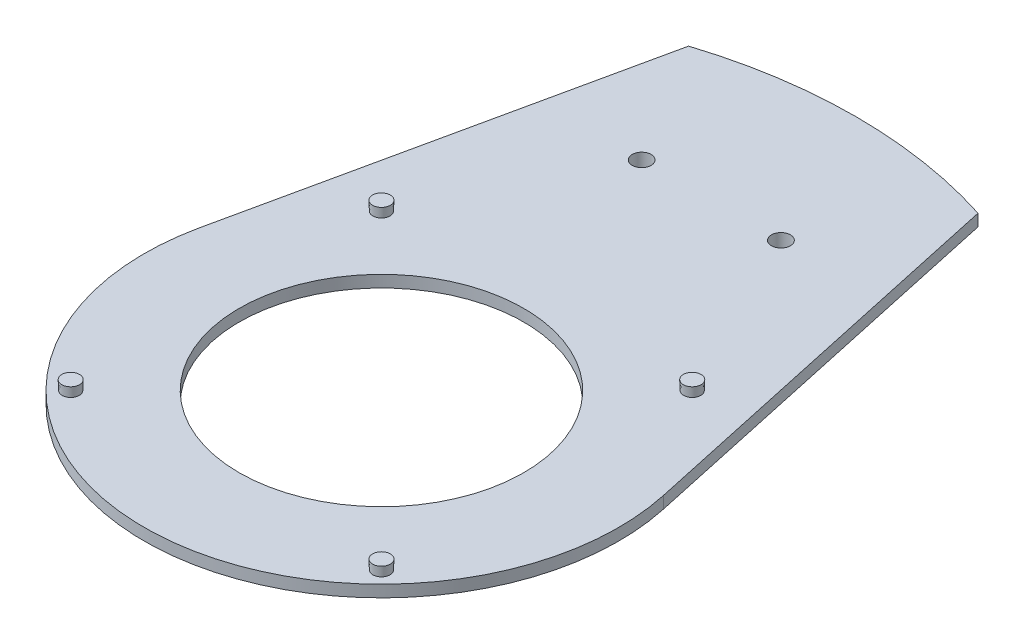
SolidWorks part; units mm, degrees
ref_plane "Front Plane" through (0, 0, 0) normal (0, 0, 1) x (1, 0, 0)
ref_plane "Top Plane" through (0, 0, 0) normal (0, 1, 0) x (1, 0, 0)
ref_plane "Right Plane" through (0, 0, 0) normal (1, 0, 0) x (0, 0, -1)
sketch "Sketch1" plane through (0, 0, 0) normal (0, 1, 0) x (1, 0, 0)
  line L7 (-38, -38) -> (38, -38) construction
  line L8 (-38, -38) -> (-38, 38) construction
  line L9 (-38, 38) -> (38, 38) construction
  line L10 (38, -38) -> (38, 38) construction
  circle A0 centre (0, 0) radius 30
  circle A1 centre (0, 0) radius 100
  point P32 (0, 0)
  dimension "D1" = 60
  dimension "D3" = 200
  dimension "D2" = 76
extrude "Boss-Extrude1" add sketch "Sketch1" along normal blind 2.5
sketch "Sketch2" plane through (0, 2.5, 0) normal (0, 1, 0) x (1, 0, 0)
  line L0 (-32.75, -38) -> (-32.75, 38) construction
  line L3 (-38, 32.75) -> (38, 32.75) construction
  line L6 (32.75, -38) -> (32.75, 38) construction
  line L7 (-38, -32.75) -> (38, -32.75) construction
  line L9 (-38, -38) -> (-38, 38) construction
  line L10 (-38, -38) -> (38, -38) construction
  line L11 (-38, 38) -> (38, 38) construction
  line L12 (38, -38) -> (38, 38) construction
  circle A0 centre (-32.75, 32.75) radius 1.8
  circle A1 centre (-32.75, -32.75) radius 1.8
  circle A2 centre (32.75, -32.75) radius 1.8
  circle A3 centre (32.75, 32.75) radius 1.8
  dimension "D5" = 3.6
  dimension "D1" = 65.5
  dimension "D2" = 5.25
  dimension "D3" = 65.5
  dimension "D4" = 5.25
extrude "Boss-Extrude2" add sketch "Sketch2" along normal blind 2 draft 2 draft outward yes
sketch "Sketch3" plane through (0, 0, 0) normal (0, 1, 0) x (1, 0, 0)
  line L0 (0, 0) -> (0, 47) construction
  line L3 (23.5, 40.7032) -> (24.25, 42.0022)
  line L5 (40.7032, 23.5) -> (42.0022, 24.25)
  line L6 (40.7032, -23.5) -> (42.0022, -24.25)
  line L7 (23.5, -40.7032) -> (24.25, -42.0022)
  line L8 (-23.5, -40.7032) -> (-24.25, -42.0022)
  line L9 (-40.7032, -23.5) -> (-42.0022, -24.25)
  line L10 (-40.7032, 23.5) -> (-42.0022, 24.25)
  line L11 (-23.5, 40.7032) -> (-24.25, 42.0022)
  arc A3 (40.7032, 23.5) -> (23.5, 40.7032) centre (0, 0) ccw
  arc A4 (42.0022, 24.25) -> (24.25, 42.0022) centre (0, 0) ccw
  circle A6 centre (0, 0) radius 48.5 construction
  circle A8 centre (0, 0) radius 47 construction
  arc A9 (23.5, -40.7032) -> (40.7032, -23.5) centre (0, 0) ccw
  arc A10 (24.25, -42.0022) -> (42.0022, -24.25) centre (0, 0) ccw
  arc A11 (-40.7032, -23.5) -> (-23.5, -40.7032) centre (0, 0) ccw
  arc A12 (-42.0022, -24.25) -> (-24.25, -42.0022) centre (0, 0) ccw
  arc A13 (-23.5, 40.7032) -> (-40.7032, 23.5) centre (0, 0) ccw
  arc A14 (-24.25, 42.0022) -> (-42.0022, 24.25) centre (0, 0) ccw
  point P4 (0, 0)
  point P5 (44.2917, 13.5413)
  point P7 (44.9463, 13.7415)
  point P8 (48.5, 0)
  point P9 (48.8155, 0)
  point P28 (0, 0)
  point P31 (0, 0)
  dimension "D2" = 1.5
  dimension "D1" = 47
  dimension "D3" = 30
  dimension "D4" = 30
extrude "Boss-Extrude3" [suppressed] add sketch "Sketch3" against normal blind 40
sketch "Sketch4" plane through (0, 0, 0) normal (0, -1, 0) x (1, 0, 0)
  line L0 (0, 0) -> (14.6751, -69.5179) construction
  line L1 (0, 0) -> (-14.6751, -69.5179) construction
  line L2 (0, 0) -> (0, -100) construction
  circle A0 centre (14.6751, -69.5179) radius 2
  circle A1 centre (-14.6751, -69.5179) radius 2
  circle A2 centre (0, 0) radius 100 construction
  dimension "D3" = 4
  dimension "D1" = 71.05
  dimension "D2" = 23.84
  dimension "D4" = 11.92
sketch "Sketch5" plane through (0, 0, 0) normal (0, -1, 0) x (1, 0, 0)
  line L0 (21.5, -69.45) -> (-21.5, -69.45)
  line L1 (21.5, -69.45) -> (21.5, -84.45)
  line L2 (-21.5, -69.45) -> (-21.5, -84.45)
  line L3 (21.5, -84.45) -> (-21.5, -84.45)
  line L4 (-14.6751, -69.5179) -> (14.6751, -69.5179) construction
  line L5 (21.5, -69.45) -> (-21.5, -69.45)
  line L6 (21.5, -69.45) -> (21.5, -54.45)
  line L7 (-21.5, -69.45) -> (-21.5, -54.45)
  line L8 (21.5, -54.45) -> (-21.5, -54.45)
  point P8 (0, -69.5179)
  dimension "D1" = 69.45
  dimension "D2" = 43
  dimension "D3" = 21.5
  dimension "D4" = 15
  dimension "D5" = 15
extrude "Boss-Extrude4" add sketch "Sketch5" along normal blind 2.35
extrude "Cut-Extrude1" cut sketch "Sketch4" against normal through all both and the other way through all contours A1 | A0
sketch "Sketch6" plane through (0, 0, 0) normal (0, -1, 0) x (1, 0, 0)
  line L0 (30.5, -95.2352) -> (30.5, -39.6201)
  line L1 (-30.5, -95.2352) -> (-30.5, -39.6201)
  line L2 (-21.5, -84.45) -> (-21.5, -54.45) construction
  line L3 (21.5, -84.45) -> (21.5, -54.45) construction
  line L4 (21.5, -84.45) -> (21.5, -54.45) construction
  line L5 (30.5, -95.2352) -> (48.8631, -10.6019)
  line L6 (-30.5, -95.2352) -> (-48.8631, -10.6019)
  circle A0 centre (0, 0) radius 100 construction
  circle A1 centre (0, 0) radius 100
  circle A2 centre (0, 0) radius 50
  circle M5 centre (0, 0) radius 100
  dimension "D2" = 9
  dimension "D3" = 9
  dimension "D1" = 50
extrude "Cut-Extrude2" cut sketch "Sketch6" against normal through all contours A2 L0 L1 M5
